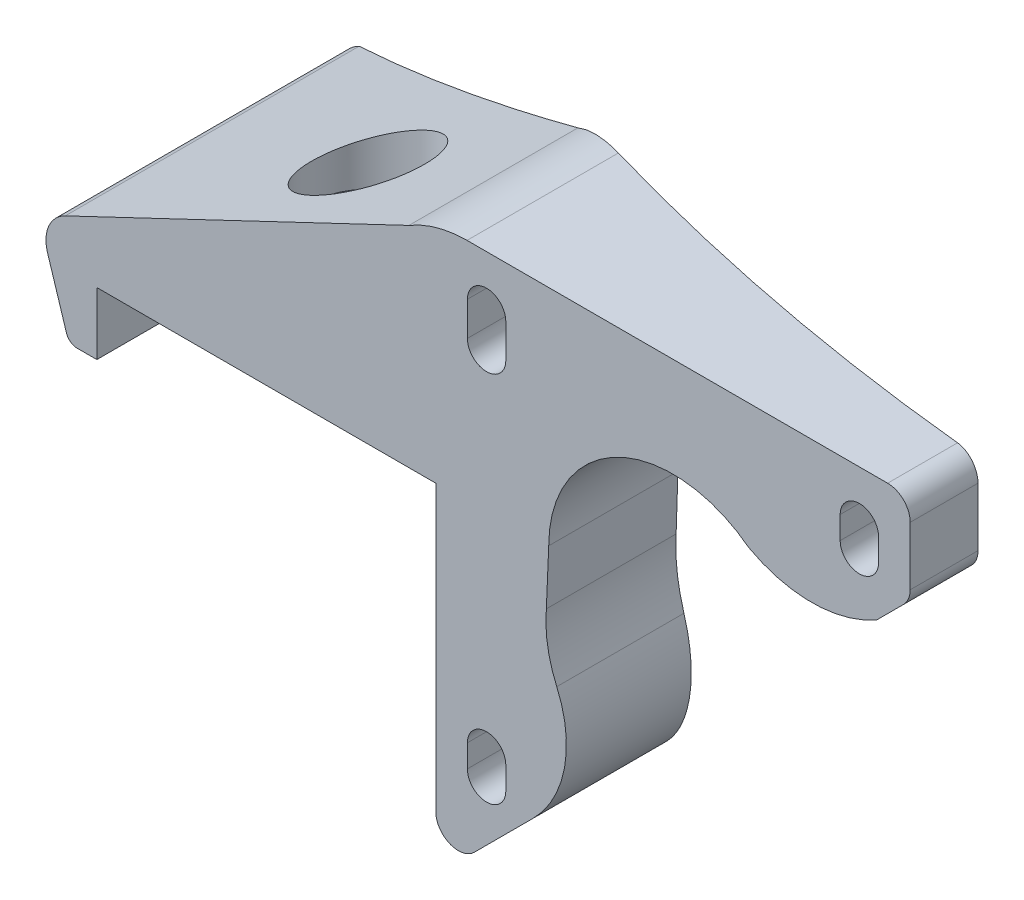
SolidWorks part; units mm, degrees
ref_plane "Plano frontal" through (0, 0, 0) normal (0, 0, 1) x (1, 0, 0)
ref_plane "Plano superior" through (0, 0, 0) normal (0, 1, 0) x (1, 0, 0)
ref_plane "Plano direito" through (0, 0, 0) normal (1, 0, 0) x (0, 0, -1)
sketch "Esboço1" plane through (0, 0, 0) normal (0, 0, 1) x (1, 0, 0)
  line L0 (4.5, 3.5) -> (37.5, -4.881) construction
  line L2 (0, 0) -> (0, 42) construction
  line L3 (0, 42) -> (42, 42) construction
  line L4 (42, -10.6667) -> (42, 42) construction
  line L5 (37.5, -4.881) -> (37.5, 37.5) construction
  line L6 (4.5, 37.5) -> (37.5, 37.5) construction
  line L7 (4.5, 3.5) -> (4.5, 37.5) construction
  line L8 (-30, 24) -> (-2.3751, 40.5749)
  line L9 (0, 22) -> (-30, 22) construction
  line L10 (0, 22) -> (0, -8) construction
  line L11 (0, -8) -> (-30, -8) construction
  line L12 (-30, 22) -> (-30, -8) construction
  line L13 (2.7698, 42) -> (40, 42)
  line L14 (42, 40) -> (42, 34.8284)
  line L15 (41.4142, 33.4142) -> (36.6706, 28.6706)
  line L17 (0, 0) -> (0, 22)
  line L18 (0, 22) -> (-30, 22)
  line L19 (-30, 22) -> (-30, 24)
  line L20 (4.5, 37.5) -> (37.5, -4.881) construction
  line L21 (37.5, -4.881) -> (37.5, 37.5) construction
  line L22 (37.5, 37.5) -> (4.5, 3.5) construction
  line L23 (8.6389, 0.6389) -> (8, 0)
  line L24 (4.5, 37.5) -> (4.5, 34.5) construction
  line L25 (6.2, 37.5) -> (6.2, 34.5)
  line L26 (2.8, 37.5) -> (2.8, 34.5)
  line L27 (37.5, 37.5) -> (37.5, 35.5) construction
  line L28 (39.2, 37.5) -> (39.2, 35.5)
  line L29 (35.8, 37.5) -> (35.8, 35.5)
  line L30 (4.5, 3.5) -> (4.5, 1.5) construction
  line L31 (6.2, 3.5) -> (6.2, 1.5)
  line L32 (2.8, 3.5) -> (2.8, 1.5)
  line L33 (8, 0) -> (6.2, -1.8)
  line L34 (6.2, -1.8) -> (3.4142, -4.5858)
  line L35 (0, -3.1716) -> (0, 0)
  line L36 (0, 0) -> (42, -10.6667) construction
  line L37 (8, 0) -> (42, -10.6667) construction
  arc A0 (25.5527, 26.5972) -> (10.7124, 11.7568) centre (21, 16.3095) ccw
  arc A1 (36.6706, 28.6706) -> (25.5527, 26.5972) centre (29.5996, 35.7417) cw
  arc A2 (8.6389, 0.6389) -> (10.7124, 11.7568) centre (1.5678, 7.71) ccw
  arc A3 (6.2, 37.5) -> (2.8, 37.5) centre (4.5, 37.5) ccw
  arc A4 (2.8, 34.5) -> (6.2, 34.5) centre (4.5, 34.5) ccw
  arc A5 (39.2, 37.5) -> (35.8, 37.5) centre (37.5, 37.5) ccw
  arc A6 (35.8, 35.5) -> (39.2, 35.5) centre (37.5, 35.5) ccw
  arc A7 (6.2, 3.5) -> (2.8, 3.5) centre (4.5, 3.5) ccw
  arc A8 (2.8, 1.5) -> (6.2, 1.5) centre (4.5, 1.5) ccw
  arc A9 (-2.3751, 40.5749) -> (2.7698, 42) centre (2.7698, 32) cw
  arc A10 (3.4142, -4.5858) -> (0, -3.1716) centre (2, -3.1716) cw
  arc A11 (42, 34.8284) -> (41.4142, 33.4142) centre (40, 34.8284) cw
  arc A12 (40, 42) -> (42, 40) centre (40, 40) cw
  point P23 (4.5, 36)
  point P29 (37.5, 36.5)
  point P35 (4.5, 2.5)
  point P50 (42, 34)
  dimension "D10" = 22.5
  dimension "D11" = 10
  dimension "D12" = 1.7
  dimension "D15" = 1.7
  dimension "D16" = 1.7
  dimension "D18" = 10
  dimension "D19" = 2
  dimension "D1" = 42
  dimension "D2" = 42
  dimension "D4" = 30
  dimension "D5" = 30
  dimension "D6" = 20
  dimension "D7" = 2
  dimension "D8" = 8
  dimension "D9" = 8
  dimension "D13" = 3
  dimension "D14" = 1
  dimension "D17" = 2
  dimension "D3" = 4.5
extrude "Ressalto-extrusão1" add sketch "Esboço1" along normal blind 6
sketch "Esboço2" plane through (0, 42, 0) normal (0, 1, 0) x (1, 0, 0)
  line L0 (-30, 0) -> (-30, 20)
  line L1 (42, 0) -> (-30, 0)
  arc A0 (-30, 20) -> (42, 0) centre (60.66, 206.7761) ccw
  dimension "D1" = 20
extrude "Ressalto-extrusão2" add sketch "Esboço2" against normal through all
sketch "Esboço3" plane through (0, 0, 0) normal (0, 0, 1) x (1, 0, 0)
  line L2 (6.2, 34.5) -> (6.2, 37.5)
  line L3 (6.2, 34.5) -> (6.2, 37.5)
  line L4 (0, 22) -> (-30, 22)
  line L5 (-30, 22) -> (-30, -5.1716)
  line L6 (-30, -5.1716) -> (2, -5.1716)
  line L9 (-30, 22) -> (-30, -5.1716)
  line L10 (-30, -5.1716) -> (2, -5.1716)
  line L12 (2, -5.1716) -> (42, -5.1716)
  line L13 (42, -5.1716) -> (42, 34.8284)
  line L14 (41.4142, 33.4142) -> (36.6706, 28.6706)
  line L15 (41.4142, 33.4142) -> (36.6706, 28.6706)
  line L16 (2, -5.1716) -> (42, -5.1716)
  line L17 (42, -5.1716) -> (42, 34.8284)
  line L22 (39.2, 35.5) -> (39.2, 37.5)
  line L23 (39.2, 35.5) -> (39.2, 37.5)
  line L26 (6.2, 1.5) -> (6.2, 3.5)
  line L27 (6.2, 1.5) -> (6.2, 3.5)
  line L30 (2.8, 37.5) -> (2.8, 34.5)
  line L31 (-30, 24) -> (-2.3751, 40.5749)
  line L32 (2.7698, 42) -> (-30, 42)
  line L33 (-30, 42) -> (-30, 24)
  line L35 (2.7698, 42) -> (-30, 42)
  line L36 (-30, 42) -> (-30, 24)
  line L37 (2.8, 37.5) -> (2.8, 34.5)
  line L38 (0, 22) -> (-30, 22)
  line L40 (8.6389, 0.6389) -> (3.4142, -4.5858)
  line L41 (8.6389, 0.6389) -> (3.4142, -4.5858)
  line L42 (35.8, 37.5) -> (35.8, 35.5)
  line L43 (35.8, 37.5) -> (35.8, 35.5)
  line L44 (2.8, 3.5) -> (2.8, 1.5)
  line L45 (2.8, 3.5) -> (2.8, 1.5)
  line L47 (-30, 24) -> (-2.3751, 40.5749)
  line L63 (0, -3.1716) -> (0, 22)
  line L64 (0, -3.1716) -> (0, 22)
  arc A1 (0, -3.1716) -> (2, -5.1716) centre (2, -3.1716) ccw
  arc A3 (0, -3.1716) -> (2, -5.1716) centre (2, -3.1716) ccw
  arc A4 (2.7698, 42) -> (-2.3751, 40.5749) centre (2.7698, 32) ccw
  arc A5 (2.8, 34.5) -> (6.2, 34.5) centre (4.5, 34.5) ccw
  arc A7 (2.8, 34.5) -> (6.2, 34.5) centre (4.5, 34.5) ccw
  arc A8 (6.2, 37.5) -> (2.8, 37.5) centre (4.5, 37.5) ccw
  arc A9 (2, -5.1716) -> (3.4142, -4.5858) centre (2, -3.1716) ccw
  arc A10 (2, -5.1716) -> (3.4142, -4.5858) centre (2, -3.1716) ccw
  arc A11 (41.4142, 33.4142) -> (42, 34.8284) centre (40, 34.8284) ccw
  arc A18 (41.4142, 33.4142) -> (42, 34.8284) centre (40, 34.8284) ccw
  arc A19 (25.5527, 26.5972) -> (36.6706, 28.6706) centre (29.5996, 35.7417) ccw
  arc A22 (25.5527, 26.5972) -> (36.6706, 28.6706) centre (29.5996, 35.7417) ccw
  arc A23 (25.5527, 26.5972) -> (10.7124, 11.7568) centre (21, 16.3095) ccw
  arc A27 (25.5527, 26.5972) -> (10.7124, 11.7568) centre (21, 16.3095) ccw
  arc A28 (8.6389, 0.6389) -> (10.7124, 11.7568) centre (1.5678, 7.71) ccw
  arc A29 (8.6389, 0.6389) -> (10.7124, 11.7568) centre (1.5678, 7.71) ccw
  arc A30 (6.2, 37.5) -> (2.8, 37.5) centre (4.5, 37.5) ccw
  arc A31 (35.8, 35.5) -> (39.2, 35.5) centre (37.5, 35.5) ccw
  arc A32 (35.8, 35.5) -> (39.2, 35.5) centre (37.5, 35.5) ccw
  arc A33 (39.2, 37.5) -> (35.8, 37.5) centre (37.5, 37.5) ccw
  arc A34 (39.2, 37.5) -> (35.8, 37.5) centre (37.5, 37.5) ccw
  arc A35 (2.8, 1.5) -> (6.2, 1.5) centre (4.5, 1.5) ccw
  arc A36 (2.8, 1.5) -> (6.2, 1.5) centre (4.5, 1.5) ccw
  arc A37 (6.2, 3.5) -> (2.8, 3.5) centre (4.5, 3.5) ccw
  arc A38 (6.2, 3.5) -> (2.8, 3.5) centre (4.5, 3.5) ccw
  arc A39 (2.7698, 42) -> (-2.3751, 40.5749) centre (2.7698, 32) ccw
  dimension "D1" = 0
  dimension "D2" = 0
  dimension "D3" = 0
  dimension "D4" = 0
  dimension "D5" = 0
  dimension "D6" = 0
extrude "Corte-extrusão1" cut sketch "Esboço3" against normal blind 36 contours A39 L35 L36 L47 | L3 A30 L37 A7 | L23 A34 L43 A32 | A29 L41 A10 L16 L17 A18 L15 A22 A27 | L27 A38 L45 A36
sketch "Esboço4" plane through (0, 0, 0) normal (0, 0, 1) x (1, 0, 0)
  line L2 (42, 40) -> (42, 42)
  line L3 (42, 42) -> (40, 42)
  line L4 (42, 40) -> (42, 42)
  line L5 (42, 42) -> (40, 42)
  arc A1 (42, 40) -> (40, 42) centre (40, 40) ccw
  arc A3 (42, 40) -> (40, 42) centre (40, 40) ccw
  dimension "D1" = 0
extrude "Corte-extrusão2" cut sketch "Esboço4" against normal blind 6
ref_plane "Plano1" through (0, 0, 1) normal (0, 0, 1) x (1, 0, 0)
sketch "Esboço5" plane through (0, 0, 1) normal (0, 0, 1) x (1, 0, 0)
  line L36 (1.3, 37.5) -> (1.3, 34.5)
  line L37 (7.7, 34.5) -> (7.7, 37.5)
  line L38 (1.3, 37.5) -> (1.3, 34.5)
  line L39 (7.7, 34.5) -> (7.7, 37.5)
  line L46 (40.2, 35.5) -> (40.2, 37.5)
  line L47 (34.8, 37.5) -> (34.8, 35.5)
  line L48 (40.2, 35.5) -> (40.2, 37.5)
  line L49 (34.8, 37.5) -> (34.8, 35.5)
  line L56 (1.8, 3.5) -> (1.8, 1.5)
  line L57 (7.2, 1.5) -> (7.2, 3.5)
  line L58 (1.8, 3.5) -> (1.8, 1.5)
  line L59 (7.2, 1.5) -> (7.2, 3.5)
  arc A32 (1.3, 34.5) -> (7.7, 34.5) centre (4.5, 34.5) ccw
  arc A33 (7.7, 37.5) -> (1.3, 37.5) centre (4.5, 37.5) ccw
  arc A34 (1.3, 34.5) -> (7.7, 34.5) centre (4.5, 34.5) ccw
  arc A35 (7.7, 37.5) -> (1.3, 37.5) centre (4.5, 37.5) ccw
  arc A40 (34.8, 35.5) -> (40.2, 35.5) centre (37.5, 35.5) ccw
  arc A41 (40.2, 37.5) -> (34.8, 37.5) centre (37.5, 37.5) ccw
  arc A42 (34.8, 35.5) -> (40.2, 35.5) centre (37.5, 35.5) ccw
  arc A43 (40.2, 37.5) -> (34.8, 37.5) centre (37.5, 37.5) ccw
  arc A48 (1.8, 1.5) -> (7.2, 1.5) centre (4.5, 1.5) ccw
  arc A49 (7.2, 3.5) -> (1.8, 3.5) centre (4.5, 3.5) ccw
  arc A50 (1.8, 1.5) -> (7.2, 1.5) centre (4.5, 1.5) ccw
  arc A51 (7.2, 3.5) -> (1.8, 3.5) centre (4.5, 3.5) ccw
  dimension "D1" = 1.5
  dimension "D2" = 1
  dimension "D3" = 1
extrude "Corte-extrusão3" cut sketch "Esboço5" against normal through all
sketch "Esboço6" plane through (0, 22, 0) normal (0, -1, 0) x (1, 0, 0)
  line L0 (-30, 6) -> (-30, -20) construction
  line L1 (-30, 6) -> (0, 6) construction
  circle A0 centre (-15, -3) radius 2.75
  dimension "D2" = 5.5
  dimension "D1" = 15
  dimension "D3" = 9
extrude "Corte-extrusão4" cut sketch "Esboço6" against normal through all
ref_plane "Plano2" through (0, 29, 0) normal (0, -1, 0) x (-1, 0, 0)
sketch "Esboço7" plane through (0, 29, 0) normal (0, -1, 0) x (-1, 0, 0)
  circle A0 centre (15, 3) radius 5
  dimension "D1" = 10
extrude "Corte-extrusão5" cut sketch "Esboço7" against normal blind 16
sketch "Esboço8" plane through (0, 0, 6) normal (0, 0, 1) x (1, 0, 0)
  line L0 (-30, 22) -> (-30, 16.4759)
  line L1 (-30, 16.4759) -> (-32.4681, 16.4759)
  line L2 (-32.4681, 16.4759) -> (-35.1519, 24.9747)
  line L3 (-35.1519, 24.9747) -> (-2.3751, 40.5749)
  line L4 (-2.3751, 40.5749) -> (-30, 22)
extrude "Ressalto-extrusão3" add sketch "Esboço8" against normal blind 56
sketch "Esboço9" plane through (-19.5276, 29.0417, 0) normal (0.558, -0.8298, 0) x (0.8298, 0.558, 0)
  line L3 (20.6694, -50) -> (20.6694, -8.9602)
  line L4 (-12.6197, -20) -> (-12.6197, -50)
  line L5 (-12.6197, -50) -> (20.6694, -50)
  line L6 (20.6694, -50) -> (20.6694, -8.9602)
  line L7 (-12.6197, -20) -> (-12.6197, -50)
  line L8 (-12.6197, -50) -> (20.6694, -50)
  ellipse E1 centre (96.6292, -206.7761) end of major axis (346.815, -206.7761) minor radius 207.6163 (20.6694, -8.9602) -> (-12.6197, -20) ccw
  ellipse E2 centre (96.6292, -206.7761) end of major axis (346.815, -206.7761) minor radius 207.6163 (20.6694, -8.9602) -> (-12.6197, -20) ccw
  dimension "D1" = 0
extrude "Corte-extrusão6" cut sketch "Esboço9" against normal blind 56
sketch "Esboço10" plane through (-10.4724, -7.0417, 0) normal (0.8298, 0.558, 0) x (0, 0, -1)
  line L4 (50, 39.9503) -> (20, 39.9503)
  line L5 (20, 39.9503) -> (20, 34.9963)
  line L6 (20, 34.9963) -> (50, 34.9963)
  line L7 (50, 34.9963) -> (50, 39.9503)
  line L8 (50, 39.9503) -> (20, 39.9503)
  line L9 (20, 39.9503) -> (20, 34.9963)
  line L10 (20, 34.9963) -> (50, 34.9963)
  line L11 (50, 34.9963) -> (50, 39.9503)
  dimension "D1" = 0
extrude "Corte-extrusão7" cut sketch "Esboço10" against normal blind 56
sketch "Esboço11" plane through (-22.2918, 33.1527, 0) normal (0.558, -0.8298, 0) x (0.8298, 0.558, 0)
  line L4 (-15.3497, -20) -> (-15.3497, -50)
  line L5 (-15.3497, -50) -> (-12.6197, -50)
  line L6 (-12.6197, -50) -> (-12.6197, -20)
  line L7 (-12.6197, -20) -> (-15.3497, -20)
  line L8 (-15.3497, -20) -> (-15.3497, -50)
  line L9 (-15.3497, -50) -> (-12.6197, -50)
  line L10 (-12.6197, -50) -> (-12.6197, -20)
  line L11 (-12.6197, -20) -> (-15.3497, -20)
  dimension "D1" = 0
extrude "Corte-extrusão8" cut sketch "Esboço11" against normal blind 56
sketch "Esboço12" plane through (-19.5276, 29.0417, 0) normal (-0.558, 0.8298, 0) x (0.8298, 0.558, 0)
  line L4 (-16.8069, 50) -> (-16.8069, 20)
  line L5 (-16.8069, 20) -> (-12.6197, 20)
  line L6 (-12.6197, 20) -> (-12.6197, 50)
  line L7 (-12.6197, 50) -> (-16.8069, 50)
  line L8 (-16.8069, 50) -> (-16.8069, 20)
  line L9 (-16.8069, 20) -> (-12.6197, 20)
  line L10 (-12.6197, 20) -> (-12.6197, 50)
  line L11 (-12.6197, 50) -> (-16.8069, 50)
  dimension "D1" = 0
extrude "Corte-extrusão9" cut sketch "Esboço12" against normal blind 56
sketch "Esboço13" plane through (0, 0, -20) normal (0, 0, -1) x (-1, 0, 0)
  circle A0 centre (34.3616, 20.651) radius 7.9681
extrude "Corte-extrusão10" cut sketch "Esboço13" along normal blind 56
fillet "Filete1" radius 3 1 edges at (-35.1519, 24.9747, -7)
fillet "Filete2" radius 1 1 edges at (-32.4681, 16.4759, -7)
sketch "Esboço14" plane through (0, 29, 0) normal (0, 1, 0) x (1, 0, 0)
  circle A0 centre (-15, 3) radius 5
extrude "Corte-extrusão11" cut sketch "Esboço14" along normal blind 56
sketch "Esboço15" plane through (0, 0, 6) normal (0, 0, 1) x (1, 0, 0)
  line L0 (4.5, 39.2) -> (4.5, 5.2) construction
  line L1 (4.5, 5.2) -> (21, 22.2) construction
  line L2 (37.5, 39.2) -> (4.5, 39.2) construction
  line L3 (4.5, 39.2) -> (21, 39.2) construction
  line L4 (21, 39.2) -> (21, 22.2) construction
  line L5 (9.75, 16.3095) -> (10, 22.2)
  line L7 (36.6706, 28.6706) -> (41.4142, 33.4142) construction
  line L8 (39.0424, 31.0424) -> (40.0567, 6.9356)
  line L9 (40.0567, 6.9356) -> (14.4981, 9.6757)
  line L10 (14.4981, 9.6757) -> (9.75, 16.3095)
  line L11 (28.6612, 30.0934) -> (37.5, 39.2) construction
  arc A0 (6.2, 37.5) -> (2.8, 37.5) centre (4.5, 37.5) ccw construction
  arc A1 (6.2, 3.5) -> (2.8, 3.5) centre (4.5, 3.5) ccw construction
  arc A2 (39.2, 37.5) -> (35.8, 37.5) centre (37.5, 37.5) ccw construction
  arc A3 (27.7224, 30.9069) -> (10, 22.2) centre (21, 22.2) ccw
  arc A4 (25.5527, 26.5972) -> (10.7124, 11.7568) centre (21, 16.3095) ccw construction
  arc A5 (27.7224, 30.9069) -> (39.0424, 31.0424) centre (33.2617, 41.0522) ccw
  dimension "D1" = 22
extrude "Corte-extrusão12" cut sketch "Esboço15" against normal through all
